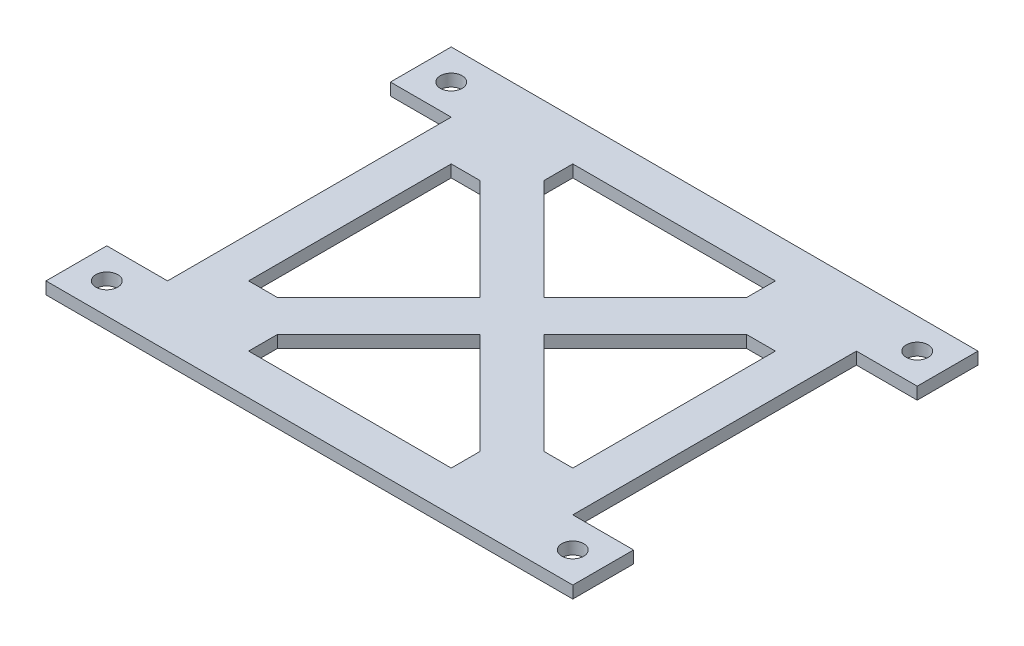
SolidWorks part; units mm, degrees
ref_plane "Front Plane" through (0, 0, 0) normal (0, 0, 1) x (1, 0, 0)
ref_plane "Top Plane" through (0, 0, 0) normal (0, 1, 0) x (1, 0, 0)
ref_plane "Right Plane" through (0, 0, 0) normal (1, 0, 0) x (0, 0, -1)
sketch "Sketch2" plane through (0, 0, 0) normal (0, 1, 0) x (1, 0, 0)
  line L1 (-49.6403, 46.6386) -> (50.3597, 46.6386)
  line L2 (-49.6403, 31.6386) -> (-49.6403, -38.3614)
  line L3 (-49.6403, -53.3614) -> (50.3597, -53.3614)
  line L4 (50.3597, 31.6386) -> (50.3597, -38.3614)
  line L5 (-24.6403, 36.6386) -> (25.3597, 36.6386)
  line L6 (-39.6403, 21.6386) -> (-39.6403, -28.3614)
  line L7 (-24.6403, -43.3614) -> (25.3597, -43.3614)
  line L8 (40.3597, 21.6386) -> (40.3597, -28.3614)
  line L12 (-24.6403, 29.5675) -> (0.3597, 4.5675)
  line L13 (-32.5692, 21.6386) -> (-7.5692, -3.3614)
  line L14 (25.3597, 29.5675) -> (0.3597, 4.5675)
  line L15 (-24.6403, -36.2903) -> (0.3597, -11.2903)
  line L16 (40.3597, -28.3614) -> (32.9391, -28.3614)
  line L17 (25.3597, -43.3614) -> (25.3597, -36.2903)
  line L18 (25.3597, 36.6386) -> (25.3597, 29.5675)
  line L19 (-39.6403, 21.6386) -> (-32.5692, 21.6386)
  line L20 (-24.6403, 36.6386) -> (-24.6403, 29.5675)
  line L21 (40.3597, 21.6386) -> (33.2887, 21.6386)
  line L22 (-24.6403, -43.3614) -> (-24.6403, -36.2903)
  line L23 (-39.6403, -28.3614) -> (-32.5692, -28.3614)
  line L24 (-7.5692, -3.3614) -> (-32.5692, -28.3614)
  line L25 (0.3597, -11.2903) -> (25.3597, -36.2903)
  line L26 (8.2887, -3.3614) -> (33.2887, -28.3614)
  line L27 (8.2887, -3.3614) -> (33.2887, 21.6386)
  line L28 (-49.6403, 31.6386) -> (-64.6403, 31.6386)
  line L29 (-49.6403, -53.3614) -> (-64.6403, -53.3614)
  line L31 (-49.6403, -38.3614) -> (-64.6403, -38.3614)
  line L32 (-64.6403, -53.3614) -> (-64.6403, -38.3614)
  line L33 (-49.6403, 46.6386) -> (-64.6403, 46.6386)
  line L34 (-64.6403, 31.6386) -> (-64.6403, 46.6386)
  line L35 (50.3597, 46.6386) -> (65.3597, 46.6386)
  line L36 (50.3597, 31.6386) -> (65.3597, 31.6386)
  line L37 (65.3597, 46.6386) -> (65.3597, 31.6386)
  line L38 (50.3597, -38.3614) -> (65.3597, -38.3614)
  line L39 (50.3597, -53.3614) -> (65.3597, -53.3614)
  line L40 (65.3597, -38.3614) -> (65.3597, -53.3614)
  circle A4 centre (-57.1403, -45.8614) radius 2.7
  circle A5 centre (-57.1403, 39.1386) radius 2.7
  circle A6 centre (57.8597, 39.1386) radius 2.7
  circle A7 centre (57.8597, -45.8614) radius 2.7
  dimension "D17" = 7.5
  dimension "D18" = 7.5
  dimension "D21" = 15
  dimension "D22" = 7.5
  dimension "D24" = 5.4
  dimension "D25" = 15
  dimension "D19" = 5.4
  dimension "D29" = 5.4
  dimension "D34" = 5.4
  dimension "D1" = 100
  dimension "D2" = 100
  dimension "D3" = 10
  dimension "D4" = 10
  dimension "D5" = 10
  dimension "D6" = 10
  dimension "D7" = 25
  dimension "D8" = 25
  dimension "D9" = 25
  dimension "D10" = 25
  dimension "D11" = 25
  dimension "D12" = 25
  dimension "D13" = 25
  dimension "D14" = 25
  dimension "D15" = 15
  dimension "D16" = 15
  dimension "D20" = 15
  dimension "D23" = 7.5
  dimension "D26" = 15
  dimension "D27" = 7.5
  dimension "D28" = 7.5
  dimension "D30" = 15
  dimension "D31" = 15
  dimension "D32" = 7.5
  dimension "D33" = 7.5
extrude "Boss-Extrude2" add sketch "Sketch2" along normal blind 3
